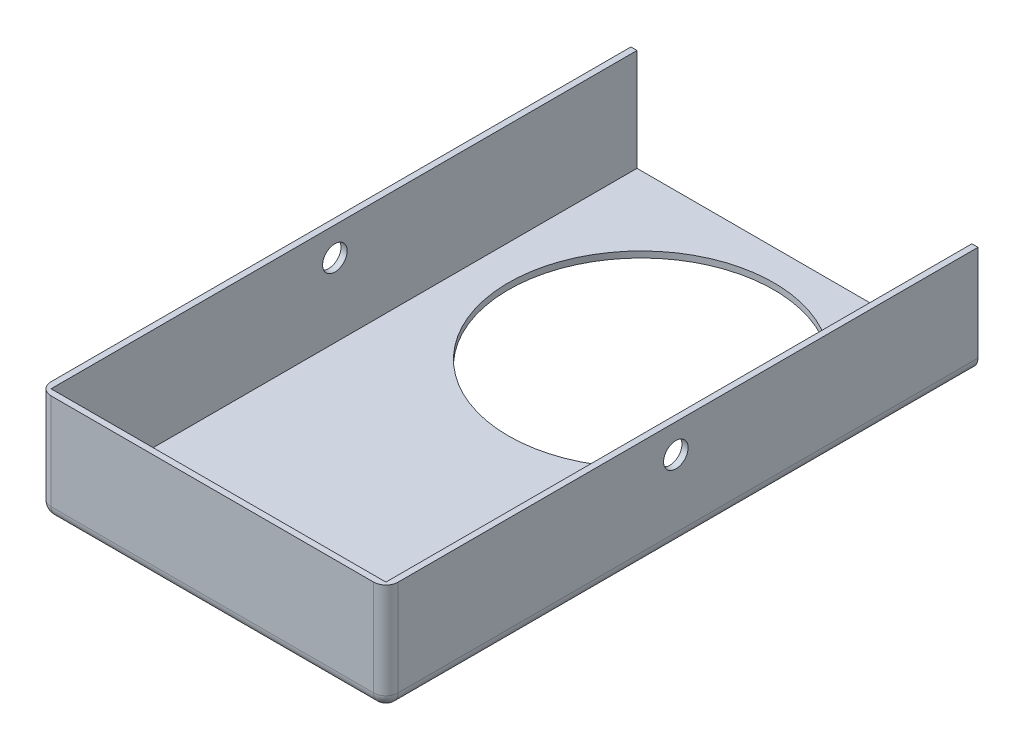
SolidWorks part; units mm, degrees
ref_plane "Front Plane" through (0, 0, 0) normal (0, 0, 1) x (1, 0, 0)
ref_plane "Top Plane" through (0, 0, 0) normal (0, 1, 0) x (1, 0, 0)
ref_plane "Right Plane" through (0, 0, 0) normal (1, 0, 0) x (0, 0, -1)
sketch "Sketch1" plane through (0, 0, 0) normal (0, 1, 0) x (1, 0, 0)
  line L1 (42.5, -72.5) -> (-42.5, -72.5)
  line L2 (42.5, -72.5) -> (42.5, 72.5)
  line L3 (42.5, 72.5) -> (-42.5, 72.5)
  line L4 (-42.5, -72.5) -> (-42.5, 72.5)
  line L5 (42.5, -72.5) -> (-42.5, 72.5) construction
  line L6 (42.5, 72.5) -> (-42.5, -72.5) construction
  circle A0 centre (0, 32.5) radius 32.5
  circle A1 centre (0, -54.5) radius 3
  point P0 (0, 0)
  dimension "D3" = 65
  dimension "D4" = 105
  dimension "D5" = 6
  dimension "D6" = 18
  dimension "D1" = 145
  dimension "D2" = 85
extrude "Boss-Extrude1" add sketch "Sketch1" along normal blind 1.5
sketch "Sketch2" plane through (0, 1.5, 0) normal (0, 1, 0) x (1, 0, 0)
  line L0 (42.5, 72.5) -> (-42.5, 72.5) construction
  line L1 (-42.5, -72.5) -> (-41, -72.5)
  line L2 (-42.5, -72.5) -> (-42.5, 72.5)
  line L3 (-42.5, 72.5) -> (-41, 72.5)
  line L4 (-41, -72.5) -> (-41, 72.5)
  line L6 (42.5, -72.5) -> (41, -72.5)
  line L7 (42.5, -72.5) -> (42.5, 72.5)
  line L8 (42.5, 72.5) -> (41, 72.5)
  line L9 (41, -72.5) -> (41, 72.5)
  line L10 (-41, -72.5) -> (41, -72.5)
  line L11 (-41, -72.5) -> (-41, -71)
  line L12 (-41, -71) -> (41, -71)
  line L13 (41, -72.5) -> (41, -71)
  line M7 (-42.5, 72.5) -> (-42.5, -72.5)
  line M8 (-42.5, -72.5) -> (42.5, -72.5)
  line M9 (42.5, -72.5) -> (42.5, 72.5)
  line M10 (42.5, 72.5) -> (-42.5, 72.5)
  dimension "D1" = 1.5
  dimension "D2" = 1.5
  dimension "D3" = 1.5
extrude "Boss-Extrude2" add sketch "Sketch2" along normal blind 25 contours L4 M8 M10 M7 | L12 L4 L9 M8 | L9 M8 M9 M10
sketch "Sketch3" plane through (0, 0, 0) normal (1, 0, 0) x (0, 0, -1)
  line L0 (-72.5, 26.5) -> (72.5, 26.5) construction
  line L1 (-72.5, 26.5) -> (-72.5, 0) construction
  circle A0 centre (-1.5, 19.5) radius 3
  dimension "D1" = 6
  dimension "D2" = 7
  dimension "D3" = 71
extrude "Cut-Extrude1" cut sketch "Sketch3" against normal through all both and the other way through all
fillet "Fillet1" radius 3 5 edges at (42.5, 13.25, 72.5) (-42.5, 13.25, 72.5) (-42.5, 0, 0) (0, 0, 72.5) (42.5, 0, 0)
sketch "Sketch4" plane through (0, 1.5, 0) normal (0, 1, 0) x (1, 0, 0)
  circle A0 centre (0, -54.5) radius 3
  circle A1 centre (0, -54.5) radius 3.5
  dimension "D1" = 7
extrude "Boss-Extrude3" add sketch "Sketch4" along normal blind 3
fillet "Fillet2" radius 1 1 edges at (0, 1.5, 58)
